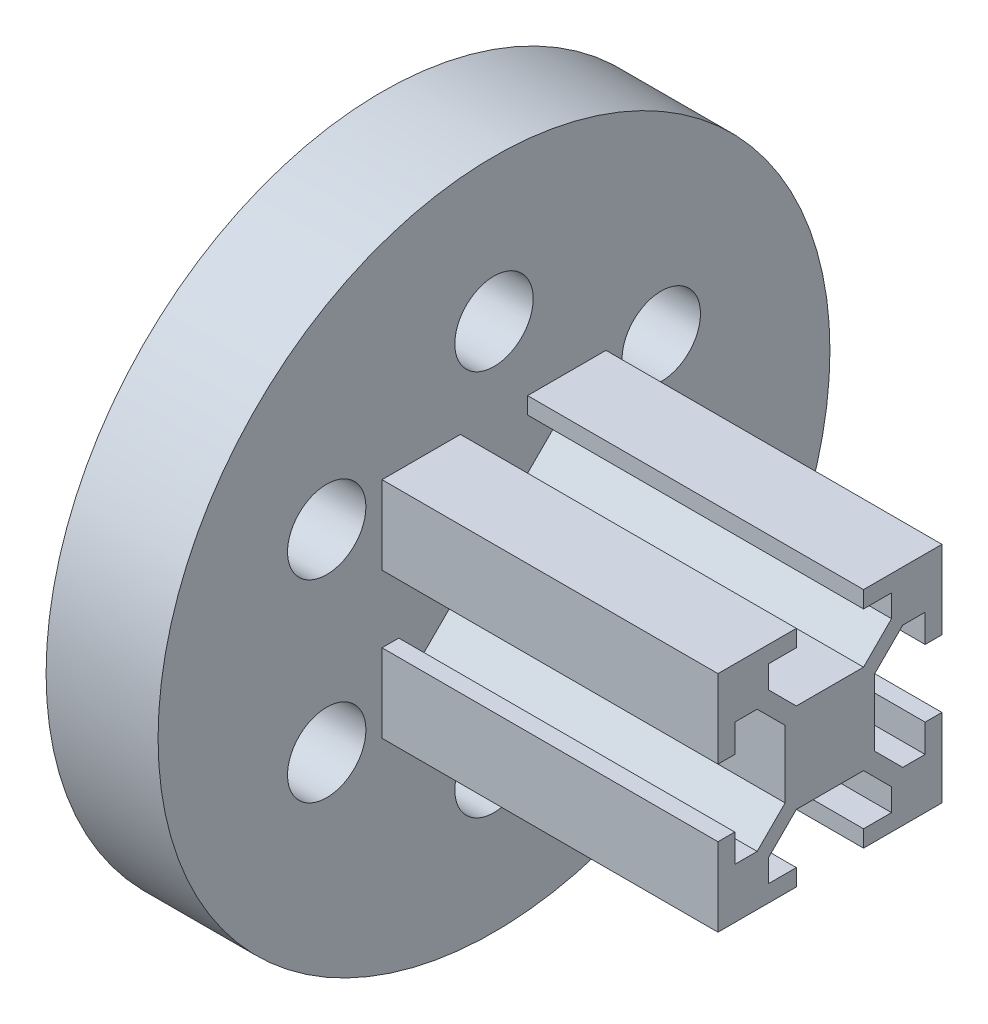
SolidWorks part; units mm, degrees
ref_plane "前视基准面" through (0, 0, 0) normal (0, 0, 1) x (1, 0, 0)
ref_plane "上视基准面" through (0, 0, 0) normal (0, 1, 0) x (1, 0, 0)
ref_plane "右视基准面" through (0, 0, 0) normal (1, 0, 0) x (0, 0, -1)
other "Configuration Table"
sketch "草图1" plane through (0, 0, 0) normal (1, 0, 0) x (0, 0, -1)
  circle A0 centre (0, 0) radius 30
  dimension "D1" = 60
extrude "凸台-拉伸1" add sketch "草图1" along normal blind 5
sketch "草图2" plane through (5, 0, 0) normal (1, 0, 0) x (0, 0, -1)
  line L1 (-10, 10) -> (10, 10)
  line L2 (-10, 10) -> (-10, -10)
  line L3 (-10, -10) -> (10, -10)
  line L4 (10, 10) -> (10, -10)
  line L5 (-10, 10) -> (10, -10) construction
  line L6 (-10, -10) -> (10, 10) construction
  point P0 (0, 0)
  dimension "D1" = 20
  dimension "D2" = 20
extrude "凸台-拉伸2" add sketch "草图2" along normal blind 30
sketch "草图4" plane through (0, 0, 0) normal (-1, 0, 0) x (0, 0, 1)
  circle A1 centre (0, 0) radius 30
  circle A2 centre (0, 0) radius 30
  dimension "D1" = 0
extrude "凸台-拉伸3" add sketch "草图4" along normal blind 5
sketch "草图5" plane through (35, 0, 0) normal (1, 0, 0) x (0, 0, -1)
  line L0 (-10, 0) -> (0, 0) construction
  line L1 (-10, 10) -> (-10, -10) construction
  line L2 (-10, 3) -> (-8.5, 3)
  line L3 (-8.5, 3) -> (-8.5, 5.5)
  line L4 (-8.5, 5.5) -> (-6.5, 5.5)
  line L5 (-6.5, 5.5) -> (-4, 3)
  line L6 (-4, 3) -> (-4, -3)
  line L7 (-6.5, -5.5) -> (-4, -3)
  line L8 (-8.5, -5.5) -> (-6.5, -5.5)
  line L9 (-8.5, -3) -> (-8.5, -5.5)
  line L10 (-10, -3) -> (-8.5, -3)
  line L11 (10, -10) -> (10, 10)
  line L12 (10, 10) -> (-10, 10)
  line L13 (-10, 10) -> (-10, -10)
  line L14 (-10, -10) -> (10, -10)
  line L15 (10, -10) -> (10, 10)
  line L16 (10, 10) -> (-10, 10)
  line L17 (-10, 10) -> (-10, -10)
  line L18 (-10, -10) -> (10, -10)
  line L19 (3, 10) -> (3, 8.5)
  line L20 (3, 8.5) -> (5.5, 8.5)
  line L21 (5.5, 8.5) -> (5.5, 6.5)
  line L22 (5.5, 6.5) -> (3, 4)
  line L23 (3, 4) -> (-3, 4)
  line L24 (-5.5, 6.5) -> (-3, 4)
  line L25 (-5.5, 8.5) -> (-5.5, 6.5)
  line L26 (-3, 8.5) -> (-5.5, 8.5)
  line L27 (-3, 10) -> (-3, 8.5)
  line L28 (10, -3) -> (8.5, -3)
  line L29 (8.5, -3) -> (8.5, -5.5)
  line L30 (8.5, -5.5) -> (6.5, -5.5)
  line L31 (6.5, -5.5) -> (4, -3)
  line L32 (4, -3) -> (4, 3)
  line L33 (6.5, 5.5) -> (4, 3)
  line L34 (8.5, 5.5) -> (6.5, 5.5)
  line L35 (8.5, 3) -> (8.5, 5.5)
  line L36 (10, 3) -> (8.5, 3)
  line L37 (-3, -10) -> (-3, -8.5)
  line L38 (-3, -8.5) -> (-5.5, -8.5)
  line L39 (-5.5, -8.5) -> (-5.5, -6.5)
  line L40 (-5.5, -6.5) -> (-3, -4)
  line L41 (-3, -4) -> (3, -4)
  line L42 (5.5, -6.5) -> (3, -4)
  line L43 (5.5, -8.5) -> (5.5, -6.5)
  line L44 (3, -8.5) -> (5.5, -8.5)
  line L45 (3, -10) -> (3, -8.5)
  point P13 (0, 0)
  point P19 (-4, 0)
  point P23 (0, 4)
  point P30 (0, 4)
  point P41 (4, 0)
  point P52 (0, -4)
  point P56 (0, 0)
  line M13 (-10, 10) -> (-10, -10)
  dimension "D2" = 3
  dimension "D3" = 11
  dimension "D4" = 6
  dimension "D5" = 1.5
  dimension "D1" = 0
  dimension "D7" = 4
extrude "切除-拉伸1" cut sketch "草图5" against normal blind 30 contours L0 L6 L5 L4 L3 L2 M13 | L0 L17 L10 L9 L8 L7 L6 | L18 L45 L44 L43 L42 L41 L40 L39 L38 L37 | L15 L36 L35 L34 L33 L32 L31 L30 L29 L28 | L16 L27 L26 L25 L24 L23 L22 L21 L20 L19
sketch "草图7" plane through (-5, 0, 0) normal (-1, 0, 0) x (0, 0, 1)
  circle A0 centre (0, 0) radius 17.25 construction
  circle A1 centre (0, -17.25) radius 2.1
  circle A2 centre (-14.9389, -8.625) radius 2.1
  circle A3 centre (-14.9389, 8.625) radius 2.1
  circle A4 centre (0, 17.25) radius 2.1
  circle A5 centre (14.9389, 8.625) radius 2.1
  circle A6 centre (14.9389, -8.625) radius 2.1
  point P18 (0, 0)
  dimension "D1" = 34.5
  dimension "D2" = 4.2
  dimension "D3" = 6
extrude "切除-拉伸2" cut sketch "草图7" against normal blind 30
sketch "草图8" plane through (5, 0, 0) normal (1, 0, 0) x (0, 0, -1)
  circle A0 centre (-14.9389, 8.625) radius 3.5
  circle A1 centre (0, 17.25) radius 3.5
  circle A2 centre (14.9389, 8.625) radius 3.5
  circle A3 centre (14.9389, -8.625) radius 3.5
  circle A4 centre (0, -17.25) radius 3.5
  circle A5 centre (-14.9389, -8.625) radius 3.5
  point P16 (0, 0)
  dimension "D1" = 7
  dimension "D2" = 6
extrude "切除-拉伸3" cut sketch "草图8" against normal blind 5
sketch "草图9" plane through (35, 0, 0) normal (1, 0, 0) x (0, 0, -1)
  line L44 (10, -10) -> (10, -3)
  line L45 (10, -3) -> (8.5, -3)
  line L46 (8.5, -3) -> (8.5, -5.5)
  line L47 (8.5, -5.5) -> (6.5, -5.5)
  line L48 (6.5, -5.5) -> (4, -3)
  line L49 (4, -3) -> (4, 3)
  line L50 (4, 3) -> (6.5, 5.5)
  line L51 (6.5, 5.5) -> (8.5, 5.5)
  line L52 (8.5, 5.5) -> (8.5, 3)
  line L53 (8.5, 3) -> (10, 3)
  line L54 (10, 3) -> (10, 10)
  line L55 (10, 10) -> (3, 10)
  line L56 (3, 10) -> (3, 8.5)
  line L57 (3, 8.5) -> (5.5, 8.5)
  line L58 (5.5, 8.5) -> (5.5, 6.5)
  line L59 (5.5, 6.5) -> (3, 4)
  line L60 (3, 4) -> (-3, 4)
  line L61 (-3, 4) -> (-5.5, 6.5)
  line L62 (-5.5, 6.5) -> (-5.5, 8.5)
  line L63 (-5.5, 8.5) -> (-3, 8.5)
  line L64 (-3, 8.5) -> (-3, 10)
  line L65 (-3, 10) -> (-10, 10)
  line L66 (-10, 10) -> (-10, 3)
  line L67 (-10, 3) -> (-8.5, 3)
  line L68 (-8.5, 3) -> (-8.5, 5.5)
  line L69 (-8.5, 5.5) -> (-6.5, 5.5)
  line L70 (-6.5, 5.5) -> (-4, 3)
  line L71 (-4, 3) -> (-4, -3)
  line L72 (-4, -3) -> (-6.5, -5.5)
  line L73 (-6.5, -5.5) -> (-8.5, -5.5)
  line L74 (-8.5, -5.5) -> (-8.5, -3)
  line L75 (-8.5, -3) -> (-10, -3)
  line L76 (-10, -3) -> (-10, -10)
  line L77 (-10, -10) -> (-3, -10)
  line L78 (-3, -10) -> (-3, -8.5)
  line L79 (-3, -8.5) -> (-5.5, -8.5)
  line L80 (-5.5, -8.5) -> (-5.5, -6.5)
  line L81 (-5.5, -6.5) -> (-3, -4)
  line L82 (-3, -4) -> (3, -4)
  line L83 (3, -4) -> (5.5, -6.5)
  line L84 (5.5, -6.5) -> (5.5, -8.5)
  line L85 (5.5, -8.5) -> (3, -8.5)
  line L86 (3, -8.5) -> (3, -10)
  line L87 (3, -10) -> (10, -10)
  line L88 (10, -10) -> (10, -3)
  line L89 (10, -3) -> (8.5, -3)
  line L90 (8.5, -3) -> (8.5, -5.5)
  line L91 (8.5, -5.5) -> (6.5, -5.5)
  line L92 (6.5, -5.5) -> (4, -3)
  line L93 (4, -3) -> (4, 3)
  line L94 (4, 3) -> (6.5, 5.5)
  line L95 (6.5, 5.5) -> (8.5, 5.5)
  line L96 (8.5, 5.5) -> (8.5, 3)
  line L97 (8.5, 3) -> (10, 3)
  line L98 (10, 3) -> (10, 10)
  line L99 (10, 10) -> (3, 10)
  line L100 (3, 10) -> (3, 8.5)
  line L101 (3, 8.5) -> (5.5, 8.5)
  line L102 (5.5, 8.5) -> (5.5, 6.5)
  line L103 (5.5, 6.5) -> (3, 4)
  line L104 (3, 4) -> (-3, 4)
  line L105 (-3, 4) -> (-5.5, 6.5)
  line L106 (-5.5, 6.5) -> (-5.5, 8.5)
  line L107 (-5.5, 8.5) -> (-3, 8.5)
  line L108 (-3, 8.5) -> (-3, 10)
  line L109 (-3, 10) -> (-10, 10)
  line L110 (-10, 10) -> (-10, 3)
  line L111 (-10, 3) -> (-8.5, 3)
  line L112 (-8.5, 3) -> (-8.5, 5.5)
  line L113 (-8.5, 5.5) -> (-6.5, 5.5)
  line L114 (-6.5, 5.5) -> (-4, 3)
  line L115 (-4, 3) -> (-4, -3)
  line L116 (-4, -3) -> (-6.5, -5.5)
  line L117 (-6.5, -5.5) -> (-8.5, -5.5)
  line L118 (-8.5, -5.5) -> (-8.5, -3)
  line L119 (-8.5, -3) -> (-10, -3)
  line L120 (-10, -3) -> (-10, -10)
  line L121 (-10, -10) -> (-3, -10)
  line L122 (-3, -10) -> (-3, -8.5)
  line L123 (-3, -8.5) -> (-5.5, -8.5)
  line L124 (-5.5, -8.5) -> (-5.5, -6.5)
  line L125 (-5.5, -6.5) -> (-3, -4)
  line L126 (-3, -4) -> (3, -4)
  line L127 (3, -4) -> (5.5, -6.5)
  line L128 (5.5, -6.5) -> (5.5, -8.5)
  line L129 (5.5, -8.5) -> (3, -8.5)
  line L130 (3, -8.5) -> (3, -10)
  line L131 (3, -10) -> (10, -10)
  dimension "D1" = 0
